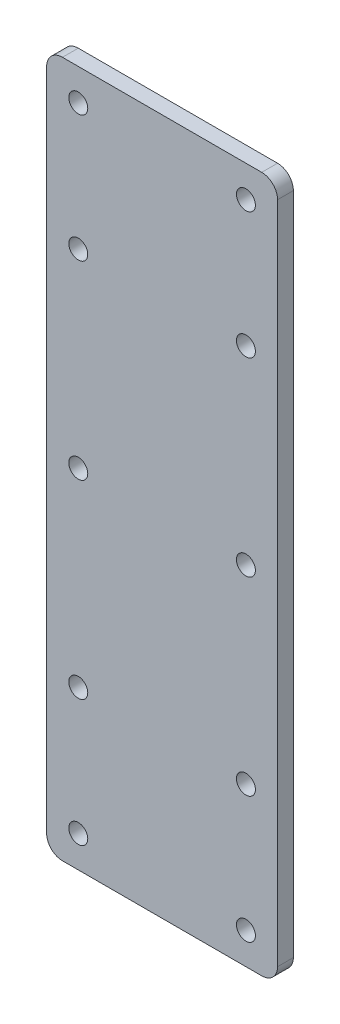
SolidWorks part; units mm, degrees
material "6061 Alloy"
ref_plane "Front Plane" through (0, 0, 0) normal (0, 0, 1) x (1, 0, 0)
ref_plane "Top Plane" through (0, 0, 0) normal (0, 1, 0) x (1, 0, 0)
ref_plane "Right Plane" through (0, 0, 0) normal (1, 0, 0) x (0, 0, -1)
sketch "Sketch2" plane through (0, 0, 0) normal (0, 0, 1) x (1, 0, 0)
  line L0 (36.5, 220) -> (36.5, 0) construction
  line L1 (5, 0) -> (68, 0)
  line L2 (0, 5) -> (0, 215)
  line L3 (5, 220) -> (68, 220)
  line L4 (73, 5) -> (73, 215)
  line L5 (10, 210) -> (63, 210)
  line L6 (10, 210) -> (10, 170)
  line L7 (10, 170) -> (63, 170)
  line L8 (63, 210) -> (63, 170)
  line L9 (0, 110) -> (73, 110) construction
  line L10 (10, 50) -> (63, 50)
  line L11 (10, 50) -> (10, 10)
  line L12 (10, 10) -> (63, 10)
  line L13 (63, 50) -> (63, 10)
  circle A0 centre (10, 210) radius 3
  circle A1 centre (63, 210) radius 3
  circle A2 centre (63, 170) radius 3
  circle A3 centre (10, 170) radius 3
  circle A4 centre (63, 50) radius 3
  circle A5 centre (10, 50) radius 3
  circle A6 centre (10, 10) radius 3
  circle A7 centre (63, 10) radius 3
  circle A8 centre (10, 110) radius 3
  circle A9 centre (63, 110) radius 3
  arc A10 (5, 0) -> (0, 5) centre (5, 5) cw
  arc A11 (68, 0) -> (73, 5) centre (68, 5) ccw
  arc A12 (68, 220) -> (73, 215) centre (68, 215) cw
  arc A13 (0, 215) -> (5, 220) centre (5, 215) cw
  point P11 (36.5, 210)
  point P20 (36.5, 10)
  point P34 (0, 0)
  dimension "D5" = 6
  dimension "D8" = 5
  dimension "D1" = 53
  dimension "D2" = 40
  dimension "D3" = 10
  dimension "D4" = 10
  dimension "D6" = 120
  dimension "D7" = 10
extrude "Boss-Extrude1" add sketch "Sketch2" along normal blind 5 contours A13 L2 A10 L1 A11 L4 A12 L3 A9 A8 A7 L12 A6 L11 A5 L10 A4 L13 A3 L6 A0 L5 A1 L8 A2 L7 | A3 L7 A2 L8 A1 L5 A0 L6 | A7 L13 A4 L10 A5 L11 A6 L12
